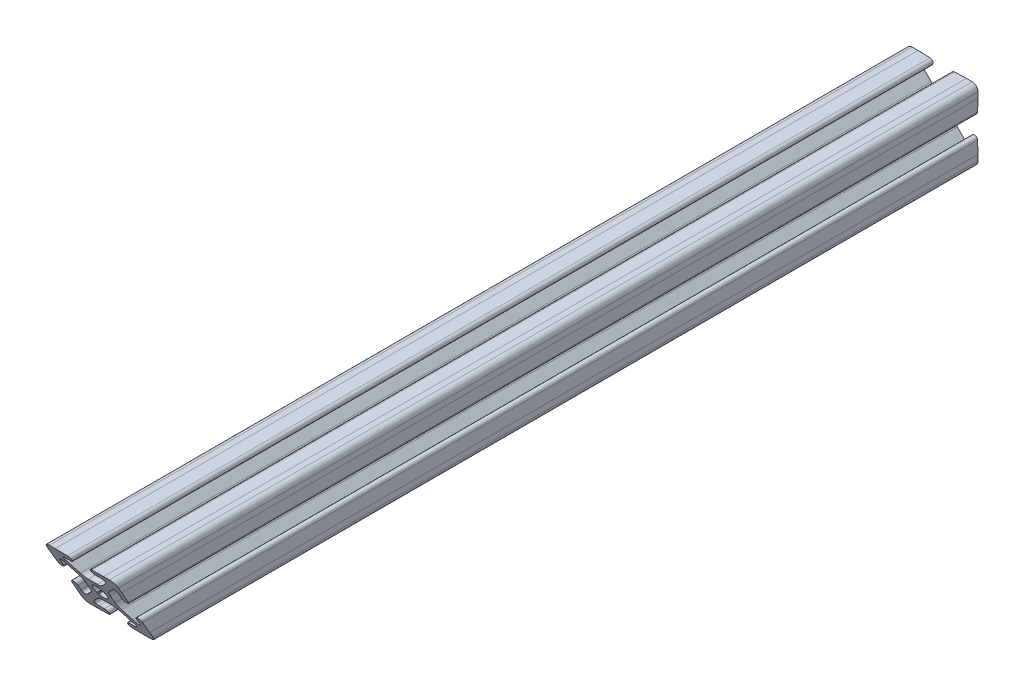
SolidWorks part; units mm, degrees
ref_plane "Front Plane" through (0, 0, 0) normal (0, 0, 1) x (1, 0, 0)
ref_plane "Top Plane" through (0, 0, 0) normal (0, 1, 0) x (1, 0, 0)
ref_plane "Right Plane" through (0, 0, 0) normal (1, 0, 0) x (0, 0, -1)
sketch "Model" plane through (0, 0, 0) normal (0, 0, 1) x (1, 0, 0)
  line L38 (50.6495, 75.4336) -> (50.2699, 75.4336)
  line L39 (50.2699, 75.4336) -> (50.2699, 75.8133)
  line L40 (50.66, 72.9999) -> (53.7746, 72.9999)
  line L41 (56.0196, 72.0699) -> (59.2642, 68.8254)
  line L42 (58.5103, 67.0916) -> (56.5725, 67.1592)
  line L43 (56.498, 65.0269) -> (60.6773, 64.881)
  line L44 (60.6773, 64.881) -> (62.7107, 64.881)
  line L45 (64.7173, 66.8876) -> (64.7173, 68.921)
  line L46 (64.7173, 68.921) -> (64.5713, 73.1002)
  line L47 (62.439, 73.0257) -> (62.5067, 71.0879)
  line L48 (60.7729, 70.334) -> (57.5283, 73.5786)
  line L49 (56.5984, 75.8237) -> (56.5984, 78.9383)
  line L50 (57.5283, 81.1833) -> (60.7729, 84.4279)
  line L51 (62.5067, 83.674) -> (62.439, 81.7362)
  line L52 (64.5713, 81.6617) -> (64.7173, 85.841)
  line L53 (64.7173, 85.841) -> (64.7173, 87.8744)
  line L54 (62.7107, 89.881) -> (60.6773, 89.881)
  line L55 (60.6773, 89.881) -> (56.498, 89.735)
  line L56 (56.5725, 87.6027) -> (58.5103, 87.6704)
  line L57 (59.2642, 85.9366) -> (56.0196, 82.692)
  line L58 (53.7746, 81.7621) -> (50.66, 81.7621)
  line L59 (48.4149, 82.692) -> (45.1703, 85.9366)
  line L60 (45.9242, 87.6704) -> (47.862, 87.6027)
  line L61 (47.9365, 89.735) -> (43.7573, 89.881)
  line L62 (43.7573, 89.881) -> (41.7239, 89.881)
  line L63 (39.7173, 87.8744) -> (39.7173, 85.841)
  line L64 (39.7173, 85.841) -> (39.8632, 81.6617)
  line L65 (41.9955, 81.7362) -> (41.9278, 83.674)
  line L66 (43.6616, 84.4279) -> (46.9062, 81.1833)
  line L67 (47.8361, 78.9383) -> (47.8361, 75.8237)
  line L68 (46.9062, 73.5786) -> (43.6616, 70.334)
  line L69 (41.9278, 71.0879) -> (41.9955, 73.0257)
  line L70 (39.8632, 73.1002) -> (39.7173, 68.921)
  line L71 (39.7173, 68.921) -> (39.7173, 66.8876)
  line L72 (41.7239, 64.881) -> (43.7573, 64.881)
  line L73 (43.7573, 64.881) -> (47.9365, 65.0269)
  line L74 (47.862, 67.1592) -> (45.9242, 67.0916)
  line L75 (45.1703, 68.8254) -> (48.4149, 72.0699)
  arc A29 (50.6495, 75.4336) -> (50.2699, 75.8133) centre (52.2173, 77.381) ccw
  arc A30 (56.0196, 72.0699) -> (53.7746, 72.9999) centre (53.7746, 69.8249) ccw
  arc A31 (58.5103, 67.0916) -> (59.2642, 68.8254) centre (58.5458, 68.1069) ccw
  arc A32 (56.5725, 67.1592) -> (56.498, 65.0269) centre (56.5353, 66.0931) ccw
  arc A33 (62.7107, 64.881) -> (64.7173, 66.8876) centre (62.7107, 66.8876) ccw
  arc A34 (64.5713, 73.1002) -> (62.439, 73.0257) centre (63.5052, 73.063) ccw
  arc A35 (60.7729, 70.334) -> (62.5067, 71.0879) centre (61.4913, 71.0525) ccw
  arc A36 (56.5984, 75.8237) -> (57.5283, 73.5786) centre (59.7734, 75.8237) ccw
  arc A37 (57.5283, 81.1833) -> (56.5984, 78.9383) centre (59.7734, 78.9383) ccw
  arc A38 (62.5067, 83.674) -> (60.7729, 84.4279) centre (61.4913, 83.7095) ccw
  arc A39 (62.439, 81.7362) -> (64.5713, 81.6617) centre (63.5052, 81.699) ccw
  arc A40 (64.7173, 87.8744) -> (62.7107, 89.881) centre (62.7107, 87.8744) ccw
  arc A41 (56.498, 89.735) -> (56.5725, 87.6027) centre (56.5353, 88.6689) ccw
  arc A42 (59.2642, 85.9366) -> (58.5103, 87.6704) centre (58.5458, 86.655) ccw
  arc A43 (53.7746, 81.7621) -> (56.0196, 82.692) centre (53.7746, 84.9371) ccw
  arc A44 (48.4149, 82.692) -> (50.66, 81.7621) centre (50.66, 84.9371) ccw
  arc A45 (45.9242, 87.6704) -> (45.1703, 85.9366) centre (45.8887, 86.655) ccw
  arc A46 (47.862, 87.6027) -> (47.9365, 89.735) centre (47.8993, 88.6689) ccw
  arc A47 (41.7239, 89.881) -> (39.7173, 87.8744) centre (41.7239, 87.8744) ccw
  arc A48 (39.8632, 81.6617) -> (41.9955, 81.7362) centre (40.9293, 81.699) ccw
  arc A49 (43.6616, 84.4279) -> (41.9278, 83.674) centre (42.9432, 83.7095) ccw
  arc A50 (47.8361, 78.9383) -> (46.9062, 81.1833) centre (44.6611, 78.9383) ccw
  arc A51 (46.9062, 73.5786) -> (47.8361, 75.8237) centre (44.6611, 75.8237) ccw
  arc A52 (41.9278, 71.0879) -> (43.6616, 70.334) centre (42.9432, 71.0525) ccw
  arc A53 (41.9955, 73.0257) -> (39.8632, 73.1002) centre (40.9293, 73.063) ccw
  arc A54 (39.7173, 66.8876) -> (41.7239, 64.881) centre (41.7239, 66.8876) ccw
  arc A55 (47.9365, 65.0269) -> (47.862, 67.1592) centre (47.8993, 66.0931) ccw
  arc A56 (45.1703, 68.8254) -> (45.9242, 67.0916) centre (45.8887, 68.1069) ccw
  arc A57 (50.66, 72.9999) -> (48.4149, 72.0699) centre (50.66, 69.8249) ccw
extrude "Boss-Extrude1" add sketch "Model" along normal blind 301.5996
sketch "Sketch2" plane through (0, 0, 0) normal (1, 0, 0) x (0, 0, -1)
  line L0 (-301.5996, 64.881) -> (-301.5996, 89.881)
  line L1 (-301.5996, 89.881) -> (-287.1658, 64.881)
  line L2 (-301.5996, 64.881) -> (0, 64.881) construction
  line L3 (-287.1658, 64.881) -> (-301.5996, 64.881)
  dimension "D1" = 30
extrude "Cut-Extrude1" cut sketch "Sketch2" along normal through all
